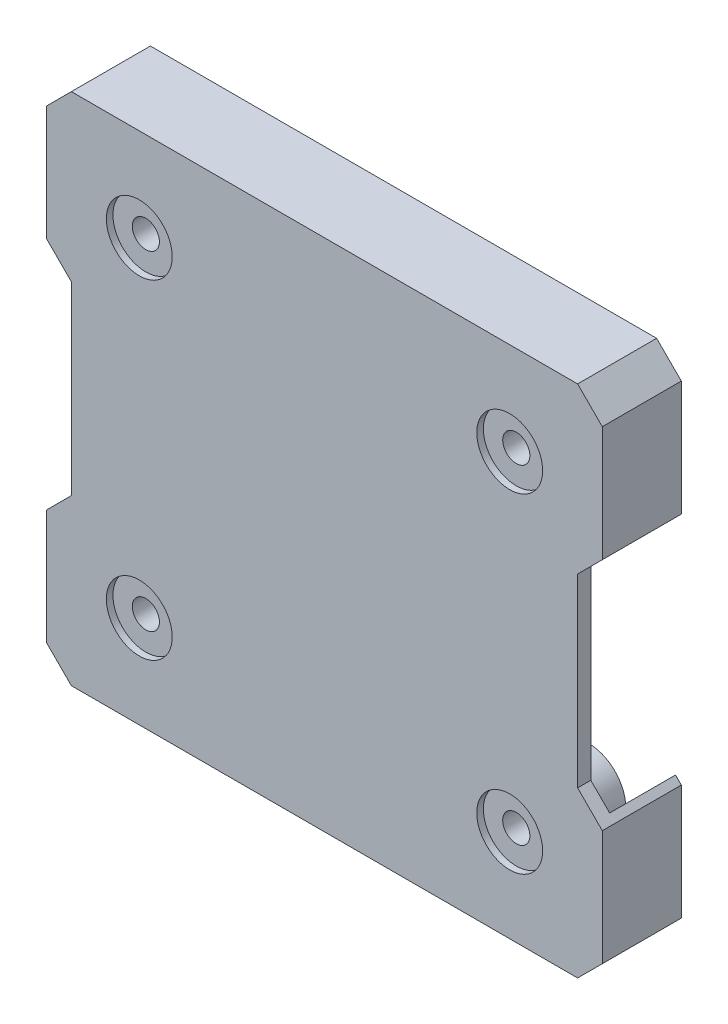
SolidWorks part; units mm, degrees
ref_plane "前视基准面" through (0, 0, 0) normal (0, 0, 1) x (1, 0, 0)
ref_plane "上视基准面" through (0, 0, 0) normal (0, 1, 0) x (1, 0, 0)
ref_plane "右视基准面" through (0, 0, 0) normal (1, 0, 0) x (0, 0, -1)
sketch "草图1" plane through (0, 0, 0) normal (0, 0, 1) x (1, 0, 0)
  line L1 (-33.75, 31.25) -> (33.75, 31.25)
  line L2 (-33.75, 31.25) -> (-33.75, -31.25)
  line L3 (-33.75, -31.25) -> (33.75, -31.25)
  line L4 (33.75, 31.25) -> (33.75, -31.25)
  line L5 (-33.75, 31.25) -> (33.75, -31.25) construction
  line L6 (-33.75, -31.25) -> (33.75, 31.25) construction
  point P0 (0, 0)
  dimension "D1" = 62.5
  dimension "D2" = 67.5
extrude "凸台-拉伸1" add sketch "草图1" along normal blind 1.6
sketch "草图2" plane through (0, 0, 1.6) normal (0, 0, 1) x (1, 0, 0)
  line L0 (-30.75, 11.25) -> (-30.75, -11.25)
  line L1 (30.75, 11.25) -> (30.75, -11.25)
  line L2 (-33.75, 31.25) -> (-33.75, -31.25) construction
  line L3 (33.75, -31.25) -> (33.75, 31.25) construction
  line L4 (-30.75, 11.25) -> (-33.75, 14.25)
  line L5 (-33.75, 14.25) -> (-33.75, -14.25)
  line L6 (-33.75, -14.25) -> (-30.75, -11.25)
  line L7 (30.75, 11.25) -> (33.75, 14.25)
  line L8 (33.75, 14.25) -> (33.75, -14.25)
  line L9 (33.75, -14.25) -> (30.75, -11.25)
  line L11 (-22.5, -20) -> (22.5, -20) construction
  line L12 (-22.5, -20) -> (-22.5, 20) construction
  line L13 (-22.5, 20) -> (22.5, 20) construction
  line L14 (22.5, -20) -> (22.5, 20) construction
  line L15 (-22.5, -20) -> (22.5, 20) construction
  line L16 (-22.5, 20) -> (22.5, -20) construction
  circle A0 centre (-22.5, 20) radius 1.65
  circle A1 centre (22.5, 20) radius 1.65
  circle A2 centre (22.5, -20) radius 1.65
  circle A3 centre (-22.5, -20) radius 1.65
  point P4 (-30.75, 0)
  point P5 (30.75, 0)
  point P11 (0, 0)
  dimension "D8" = 3.3
  dimension "D1" = 22.5
  dimension "D2" = 3
  dimension "D3" = 3
  dimension "D4" = 135
  dimension "D5" = 135
  dimension "D6" = 135
  dimension "D7" = 135
  dimension "D9" = 40
  dimension "D10" = 45
extrude "切除-拉伸1" cut sketch "草图2" against normal blind 10
chamfer "倒角1" distance 3 angle 45 4 edges at (-33.75, -31.25, 0.8) (33.75, -31.25, 0.8) (33.75, 31.25, 0.8) (-33.75, 31.25, 0.8)
sketch "草图3" plane through (0, 0, 0) normal (0, 0, -1) x (-1, 0, 0)
  line L1 (-19.9019, 20) -> (-21.201, 22.25)
  line L2 (-21.201, 22.25) -> (-23.799, 22.25)
  line L3 (-23.799, 22.25) -> (-25.0981, 20)
  line L4 (-25.0981, 20) -> (-23.799, 17.75)
  line L5 (-23.799, 17.75) -> (-21.201, 17.75)
  line L6 (-21.201, 17.75) -> (-19.9019, 20)
  line L7 (25.0981, 20) -> (23.799, 22.25)
  line L8 (23.799, 22.25) -> (21.201, 22.25)
  line L9 (21.201, 22.25) -> (19.9019, 20)
  line L10 (19.9019, 20) -> (21.201, 17.75)
  line L11 (21.201, 17.75) -> (23.799, 17.75)
  line L12 (23.799, 17.75) -> (25.0981, 20)
  line L13 (25.0981, -20) -> (23.799, -17.75)
  line L14 (23.799, -17.75) -> (21.201, -17.75)
  line L15 (21.201, -17.75) -> (19.9019, -20)
  line L16 (19.9019, -20) -> (21.201, -22.25)
  line L17 (21.201, -22.25) -> (23.799, -22.25)
  line L18 (23.799, -22.25) -> (25.0981, -20)
  line L19 (-19.9019, -20) -> (-21.201, -17.75)
  line L20 (-21.201, -17.75) -> (-23.799, -17.75)
  line L21 (-23.799, -17.75) -> (-25.0981, -20)
  line L22 (-25.0981, -20) -> (-23.799, -22.25)
  line L23 (-23.799, -22.25) -> (-21.201, -22.25)
  line L24 (-21.201, -22.25) -> (-19.9019, -20)
  circle A0 centre (-22.5, 20) radius 1.65
  circle A2 centre (22.5, 20) radius 1.65
  circle A4 centre (22.5, -20) radius 1.65
  circle A6 centre (-22.5, -20) radius 1.65
  circle A8 centre (-22.5, 20) radius 2.25 construction
  circle A9 centre (22.5, 20) radius 2.25 construction
  circle A10 centre (22.5, -20) radius 2.25 construction
  circle A11 centre (-22.5, -20) radius 2.25 construction
  dimension "D1" = 3.3
  dimension "D2" = 4.5
extrude "凸台-拉伸2" add sketch "草图3" along normal blind 4
sketch "草图4" plane through (0, 0, 1.6) normal (0, 0, 1) x (1, 0, 0)
  circle A0 centre (-22.5, 20) radius 4
  circle A1 centre (22.5, 20) radius 4
  circle A2 centre (22.5, -20) radius 4
  circle A3 centre (-22.5, -20) radius 4
  dimension "D1" = 8
extrude "切除-拉伸2" cut sketch "草图4" against normal blind 0.8
sketch "草图5" plane through (0, 0, 0) normal (0, 0, -1) x (-1, 0, 0)
  line L0 (-21.201, -22.25) -> (-19.9019, -20) construction
  line L1 (-19.9019, -20) -> (-21.201, -17.75) construction
  line L2 (-21.201, -17.75) -> (-23.799, -17.75) construction
  line L3 (-23.799, -17.75) -> (-25.0981, -20) construction
  line L4 (-25.0981, -20) -> (-23.799, -22.25) construction
  line L5 (-23.799, -22.25) -> (-21.201, -22.25) construction
  line L6 (23.799, -22.25) -> (25.0981, -20) construction
  line L7 (25.0981, -20) -> (23.799, -17.75) construction
  line L8 (23.799, -17.75) -> (21.201, -17.75) construction
  line L9 (21.201, -17.75) -> (19.9019, -20) construction
  line L10 (19.9019, -20) -> (21.201, -22.25) construction
  line L11 (21.201, -22.25) -> (23.799, -22.25) construction
  line L12 (23.799, 17.75) -> (25.0981, 20) construction
  line L13 (25.0981, 20) -> (23.799, 22.25) construction
  line L14 (23.799, 22.25) -> (21.201, 22.25) construction
  line L15 (21.201, 22.25) -> (19.9019, 20) construction
  line L16 (19.9019, 20) -> (21.201, 17.75) construction
  line L17 (21.201, 17.75) -> (23.799, 17.75) construction
  line L18 (-21.201, 17.75) -> (-19.9019, 20) construction
  line L19 (-19.9019, 20) -> (-21.201, 22.25) construction
  line L20 (-21.201, 22.25) -> (-23.799, 22.25) construction
  line L21 (-23.799, 22.25) -> (-25.0981, 20) construction
  line L22 (-25.0981, 20) -> (-23.799, 17.75) construction
  line L23 (-23.799, 17.75) -> (-21.201, 17.75) construction
  line L24 (-21.201, -22.25) -> (-19.9019, -20)
  line L25 (-19.9019, -20) -> (-21.201, -17.75)
  line L26 (-21.201, -17.75) -> (-23.799, -17.75)
  line L27 (-23.799, -17.75) -> (-25.0981, -20)
  line L28 (-25.0981, -20) -> (-23.799, -22.25)
  line L29 (-23.799, -22.25) -> (-21.201, -22.25)
  line L30 (23.799, -22.25) -> (25.0981, -20)
  line L31 (25.0981, -20) -> (23.799, -17.75)
  line L32 (23.799, -17.75) -> (21.201, -17.75)
  line L33 (21.201, -17.75) -> (19.9019, -20)
  line L34 (19.9019, -20) -> (21.201, -22.25)
  line L35 (21.201, -22.25) -> (23.799, -22.25)
  line L36 (23.799, 17.75) -> (25.0981, 20)
  line L37 (25.0981, 20) -> (23.799, 22.25)
  line L38 (23.799, 22.25) -> (21.201, 22.25)
  line L39 (21.201, 22.25) -> (19.9019, 20)
  line L40 (19.9019, 20) -> (21.201, 17.75)
  line L41 (21.201, 17.75) -> (23.799, 17.75)
  line L42 (-21.201, 17.75) -> (-19.9019, 20)
  line L43 (-19.9019, 20) -> (-21.201, 22.25)
  line L44 (-21.201, 22.25) -> (-23.799, 22.25)
  line L45 (-23.799, 22.25) -> (-25.0981, 20)
  line L46 (-25.0981, 20) -> (-23.799, 17.75)
  line L47 (-23.799, 17.75) -> (-21.201, 17.75)
  circle A2 centre (-22.5, 20) radius 4.5
  circle A3 centre (22.5, 20) radius 4.5
  circle A4 centre (22.5, -20) radius 4.5
  circle A5 centre (-22.5, -20) radius 4.5
  dimension "D1" = 9
extrude "凸台-拉伸3" add sketch "草图5" along normal blind 6
sketch "草图6" plane through (0, 0, 0) normal (0, 0, -1) x (-1, 0, 0)
  line L0 (-30.3358, -30.25) -> (30.3358, -30.25)
  line L1 (30.3358, -30.25) -> (32.75, -27.8358)
  line L2 (32.75, -27.8358) -> (32.75, -14.6642)
  line L3 (32.75, -14.6642) -> (29.75, -11.6642)
  line L4 (29.75, -11.6642) -> (29.75, 11.6642)
  line L5 (29.75, 11.6642) -> (32.75, 14.6642)
  line L6 (32.75, 14.6642) -> (32.75, 27.8358)
  line L7 (32.75, 27.8358) -> (30.3358, 30.25)
  line L8 (30.3358, 30.25) -> (-30.3358, 30.25)
  line L9 (-30.3358, 30.25) -> (-32.75, 27.8358)
  line L10 (-32.75, 27.8358) -> (-32.75, 14.6642)
  line L11 (-32.75, 14.6642) -> (-29.75, 11.6642)
  line L12 (-29.75, 11.6642) -> (-29.75, -11.6642)
  line L13 (-29.75, -11.6642) -> (-32.75, -14.6642)
  line L14 (-32.75, -14.6642) -> (-32.75, -27.8358)
  line L15 (-32.75, -27.8358) -> (-30.3358, -30.25)
  line L16 (-30.75, -31.25) -> (30.75, -31.25)
  line L17 (30.75, -31.25) -> (33.75, -28.25)
  line L18 (33.75, -28.25) -> (33.75, -14.25)
  line L19 (33.75, -14.25) -> (30.75, -11.25)
  line L20 (30.75, -11.25) -> (30.75, 11.25)
  line L21 (30.75, 11.25) -> (33.75, 14.25)
  line L22 (33.75, 14.25) -> (33.75, 28.25)
  line L23 (33.75, 28.25) -> (30.75, 31.25)
  line L24 (30.75, 31.25) -> (-30.75, 31.25)
  line L25 (-30.75, 31.25) -> (-33.75, 28.25)
  line L26 (-33.75, 28.25) -> (-33.75, 14.25)
  line L27 (-33.75, 14.25) -> (-30.75, 11.25)
  line L28 (-30.75, 11.25) -> (-30.75, -11.25)
  line L29 (-30.75, -11.25) -> (-33.75, -14.25)
  line L30 (-33.75, -14.25) -> (-33.75, -28.25)
  line L31 (-33.75, -28.25) -> (-30.75, -31.25)
  line L32 (-30.75, -31.25) -> (30.75, -31.25)
  line L33 (30.75, -31.25) -> (33.75, -28.25)
  line L34 (33.75, -28.25) -> (33.75, -14.25)
  line L35 (33.75, -14.25) -> (30.75, -11.25)
  line L36 (30.75, -11.25) -> (30.75, 11.25)
  line L37 (30.75, 11.25) -> (33.75, 14.25)
  line L38 (33.75, 14.25) -> (33.75, 28.25)
  line L39 (33.75, 28.25) -> (30.75, 31.25)
  line L40 (30.75, 31.25) -> (-30.75, 31.25)
  line L41 (-30.75, 31.25) -> (-33.75, 28.25)
  line L42 (-33.75, 28.25) -> (-33.75, 14.25)
  line L43 (-33.75, 14.25) -> (-30.75, 11.25)
  line L44 (-30.75, 11.25) -> (-30.75, -11.25)
  line L45 (-30.75, -11.25) -> (-33.75, -14.25)
  line L46 (-33.75, -14.25) -> (-33.75, -28.25)
  line L47 (-33.75, -28.25) -> (-30.75, -31.25)
  dimension "D1" = 0
  dimension "D2" = 1
extrude "凸台-拉伸4" add sketch "草图6" along normal blind 8
sketch "草图8" plane through (0, 0, 0) normal (0, 0, -1) x (-1, 0, 0)
  line L2 (-1.5, -11.1496) -> (-1.5, -12.1578)
  line L4 (1.5, -11.1496) -> (1.5, -12.1578)
  arc A0 (1.5, -11.1496) -> (-1.5, -11.1496) centre (0, 0) ccw
  arc A1 (1.5, -12.1578) -> (-1.5, -12.1578) centre (0, 0) ccw
  dimension "D1" = 1
  dimension "D2" = 22.5
  dimension "D3" = 1.5
  dimension "D4" = 1.5
extrude "凸台-拉伸5" add sketch "草图8" along normal blind 2
sketch "草图9" plane through (0, 0, -8) normal (0, 0, -1) x (-1, 0, 0)
  line L0 (29.75, 11.6642) -> (32.3358, 14.25)
  line L1 (-33.0429, 13.5429) -> (-32.3358, 14.25)
  line L2 (-33.75, 14.25) -> (-30.75, 11.25) construction
  line L3 (-32.75, 14.6642) -> (-29.75, 11.6642) construction
  line L4 (-33.0429, 13.5429) -> (-30.75, 11.25)
  line L5 (-30.75, 11.25) -> (-30.75, -11.25)
  line L6 (29.75, -11.6642) -> (29.75, 11.6642)
  line L7 (-32.3358, -14.25) -> (-33.0429, -13.5429)
  line L8 (-29.75, -11.6642) -> (-32.75, -14.6642) construction
  line L9 (-30.75, -11.25) -> (-33.75, -14.25) construction
  line L10 (-33.0429, -13.5429) -> (-30.75, -11.25)
  line L11 (-32.3358, -14.25) -> (-29.75, -11.6642)
  line L12 (-29.75, -11.6642) -> (-29.75, 11.6642)
  line L13 (-29.75, 11.6642) -> (-32.3358, 14.25)
  line L14 (0, 0) -> (0, -50000) construction
  line L15 (32.3358, -14.25) -> (29.75, -11.6642)
  line L16 (33.0429, -13.5429) -> (30.75, -11.25)
  line L25 (32.3358, -14.25) -> (33.0429, -13.5429)
  line L26 (30.75, 11.25) -> (30.75, -11.25)
  line L27 (33.0429, 13.5429) -> (30.75, 11.25)
  line L28 (33.0429, 13.5429) -> (32.3358, 14.25)
  dimension "D1" = 1
  dimension "D2" = 1
extrude "切除-拉伸4" cut sketch "草图9" against normal blind 8
sketch "草图10" plane through (0, 0, -6) normal (0, 0, -1) x (-1, 0, 0)
  circle A0 centre (-22.5, -20) radius 4.5 construction
  circle A1 centre (22.5, 20) radius 4.5 construction
  circle A2 centre (-22.5, 20) radius 4.5 construction
  circle A3 centre (22.5, -20) radius 4.5 construction
  circle A4 centre (-22.5, -20) radius 4.5
  circle A5 centre (22.5, 20) radius 4.5
  circle A6 centre (-22.5, 20) radius 4.5
  circle A7 centre (22.5, -20) radius 4.5
  circle A8 centre (-22.5, -20) radius 1.65 construction
  circle A9 centre (22.5, -20) radius 1.65 construction
  circle A10 centre (-22.5, 20) radius 1.65 construction
  circle A11 centre (-22.5, -20) radius 1.65
  circle A12 centre (22.5, -20) radius 1.65
  circle A13 centre (-22.5, 20) radius 1.65
  circle A14 centre (22.5, 20) radius 1.65 construction
  circle A15 centre (22.5, 20) radius 1.65
extrude "凸台-拉伸6" add sketch "草图10" along normal blind 2 and the other way blind 2
